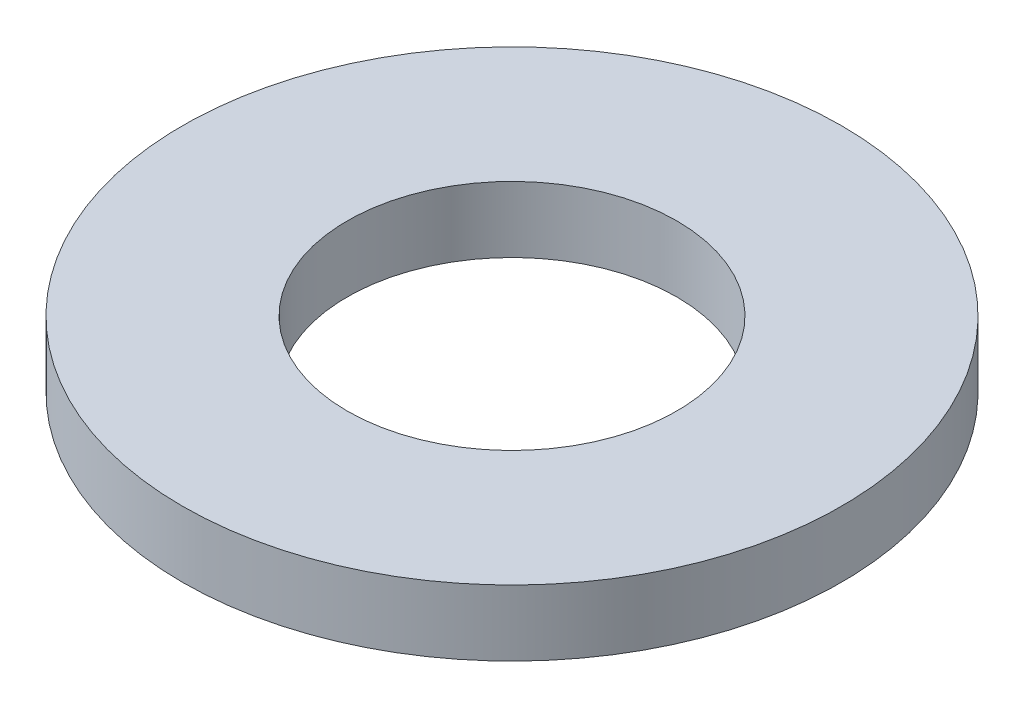
SolidWorks part; units mm, degrees
ref_plane "Front" through (0, 0, 0) normal (0, 0, 1) x (1, 0, 0)
ref_plane "Top" through (0, 0, 0) normal (0, 1, 0) x (1, 0, 0)
ref_plane "Right" through (0, 0, 0) normal (1, 0, 0) x (0, 0, -1)
other "Configuration Table"
sketch "Esquisse1" plane through (0, 0, 0) normal (0, 1, 0) x (1, 0, 0)
  circle A0 centre (0, 0) radius 2.5
  circle A1 centre (0, 0) radius 1.25
  dimension "D1" = 5
  dimension "D2" = 2.5
extrude "Boss.-Extru.1" add sketch "Esquisse1" along normal blind 0.5
